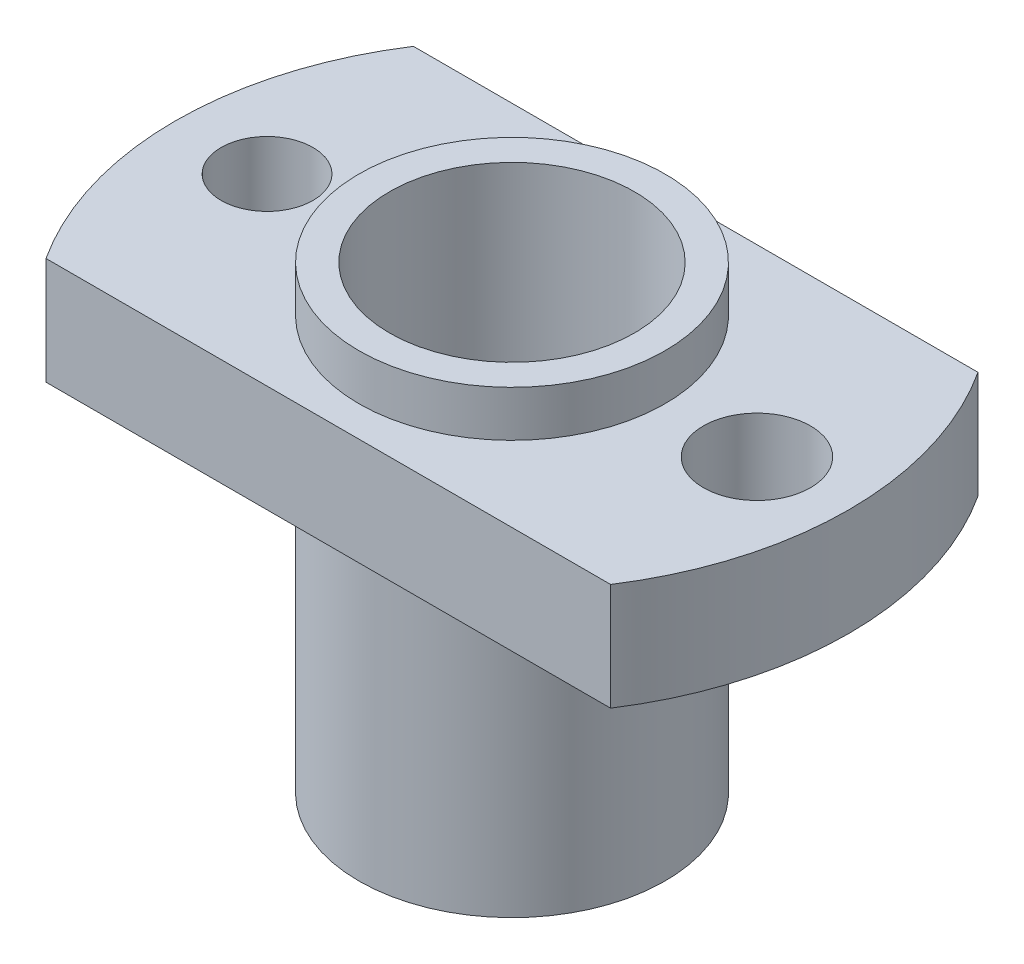
SolidWorks part; units mm, degrees
ref_plane "前视基准面" through (0, 0, 0) normal (0, 0, 1) x (1, 0, 0)
ref_plane "上视基准面" through (0, 0, 0) normal (0, 1, 0) x (1, 0, 0)
ref_plane "右视基准面" through (0, 0, 0) normal (1, 0, 0) x (0, 0, -1)
other "Configuration Table"
sketch "草图1" plane through (0, 0, 0) normal (0, 1, 0) x (1, 0, 0)
  line L0 (-9.2195, 6) -> (9.2195, 6)
  line L1 (-9.2195, -6) -> (9.2195, -6)
  arc A0 (-9.2195, 6) -> (-9.2195, -6) centre (0, 0) ccw
  arc A1 (9.2195, -6) -> (9.2195, 6) centre (0, 0) ccw
  dimension "D1" = 22
  dimension "D2" = 12
  dimension "D3" = 6
extrude "凸台-拉伸1" add sketch "草图1" along normal blind 3.5
sketch "草图2" plane through (0, 0, 0) normal (0, 1, 0) x (1, 0, 0)
  line L0 (-8, 0) -> (8, 0) construction
  circle A0 centre (8, 0) radius 1.75
  circle A1 centre (-8, 0) radius 1.5
  point P4 (0, 0)
  dimension "D1" = 3.5
  dimension "D3" = 3
  dimension "D2" = 16
extrude "切除-拉伸1" cut sketch "草图2" against normal up to surface (3.5 mm away) from surface at 3.5 up to face at (0, 0, 0) starting at face at (0, 3.5, 0)
sketch "草图3" plane through (0, 0, 0) normal (0, 1, 0) x (1, 0, 0)
  circle A0 centre (0, 0) radius 5
  dimension "D1" = 10
extrude "凸台-拉伸2" add sketch "草图3" against normal blind 10
sketch "草图4" plane through (0, 0, 0) normal (0, 1, 0) x (1, 0, 0)
  circle A0 centre (0, 0) radius 5
  dimension "D1" = 10
extrude "凸台-拉伸3" add sketch "草图4" along normal blind 1.5 from surface at 3.5 starting at face at (8, 3.5, 1.75)
sketch "草图5" plane through (0, 0, 0) normal (0, 1, 0) x (1, 0, 0)
  circle A0 centre (0, 0) radius 4
  dimension "D1" = 8
extrude "切除-拉伸2" cut sketch "草图5" along normal up to surface (15 mm away) from surface at -10 up to face at (0, 5, 5) starting at face at (0, -10, 5)
